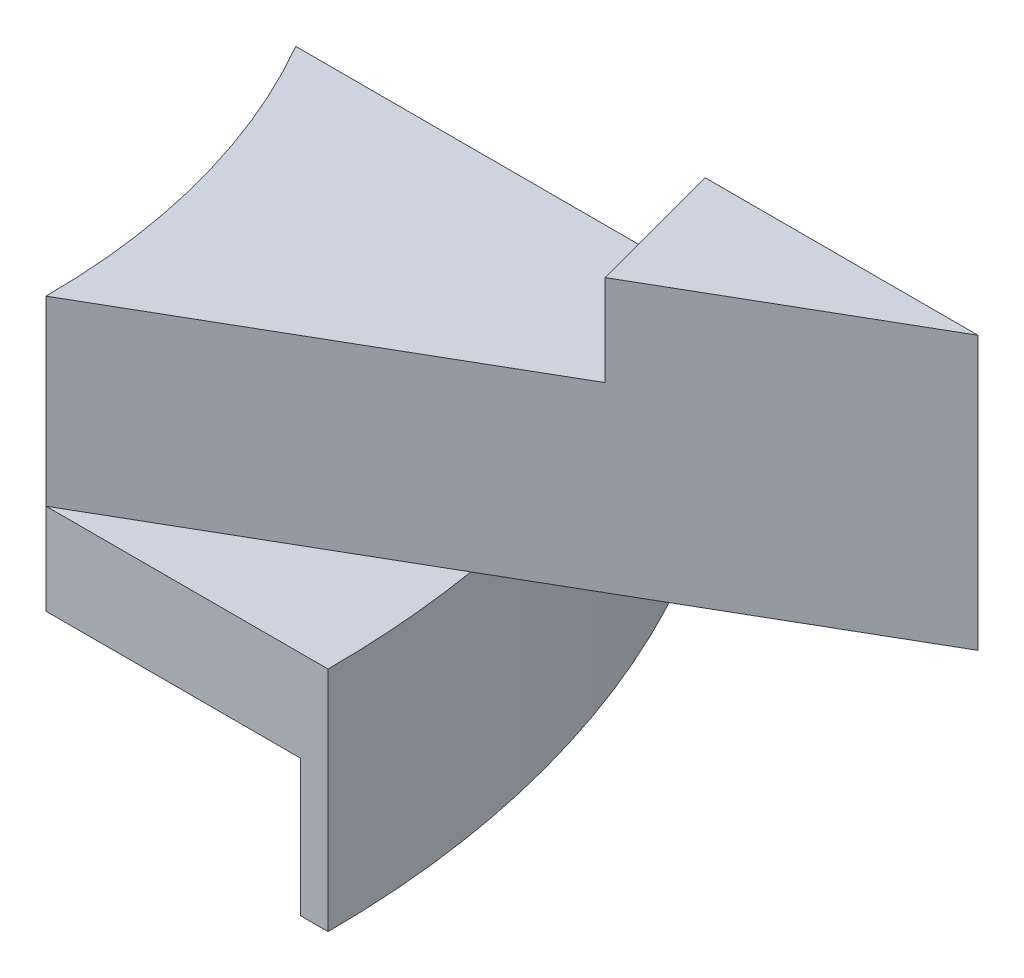
SolidWorks part; units mm, degrees
ref_plane "前视基准面" through (0, 0, 0) normal (0, 0, 1) x (1, 0, 0)
ref_plane "上视基准面" through (0, 0, 0) normal (0, 1, 0) x (1, 0, 0)
ref_plane "右视基准面" through (0, 0, 0) normal (1, 0, 0) x (0, 0, -1)
other "Configuration Table"
sketch "草图1" plane through (0, 0, 0) normal (0, 1, 0) x (1, 0, 0)
  line L1 (0, 0) -> (103, 0) construction
  line L2 (0, 0) -> (89.2006, 51.5) construction
  line L3 (64.9519, 37.5) -> (89.2006, 51.5)
  line L4 (75, 0) -> (103, 0)
  circle A0 centre (0, 0) radius 103 construction
  arc A2 (103, 0) -> (89.2006, 51.5) centre (0, 0) ccw
  arc A3 (64.9519, 37.5) -> (75, 0) centre (0, 0) cw
  dimension "D1" = 206
  dimension "D2" = 30
  dimension "D3" = 75
extrude "凸台-拉伸3" add sketch "草图1" along normal blind 10
sketch "草图5" plane through (0, 10, 0) normal (0, 1, 0) x (1, 0, 0)
  line L0 (0, 0) -> (99.4904, 26.6584) construction
  line L1 (99.4904, 26.6584) -> (204.1757, 54.7087) construction
  line L2 (64.9519, 37.5) -> (139.9519, 37.5)
  line L3 (139.9519, 37.5) -> (75, 0)
  arc A0 (103, 0) -> (89.2006, 51.5) centre (0, 0) ccw construction
  arc A1 (75, 0) -> (64.9519, 37.5) centre (0, 0) ccw
  dimension "D1" = 30
extrude "凸台-拉伸4" add sketch "草图5" along normal blind 20 contours L2 L3 A1
sketch "草图6" plane through (0, 30, 0) normal (0, 1, 0) x (1, 0, 0)
  line L0 (109.9519, 37.5) -> (139.9519, 37.5)
  line L1 (64.9519, 37.5) -> (139.9519, 37.5) construction
  line L2 (139.9519, 37.5) -> (113.9711, 22.5)
  line L3 (139.9519, 37.5) -> (75, 0) construction
  line L4 (113.9711, 22.5) -> (109.9519, 37.5)
  dimension "D1" = 30
  dimension "D2" = 30
extrude "凸台-拉伸5" add sketch "草图6" along normal blind 10
sketch "草图7" plane through (0, 10, 0) normal (0, -1, 0) x (1, 0, 0)
  line L0 (89.2006, -51.5) -> (91.7987, -53)
  line L1 (103, 0) -> (106, 0)
  arc A0 (89.2006, -51.5) -> (103, 0) centre (0, 0) ccw
  arc A1 (89.2006, -51.5) -> (103, 0) centre (0, 0) ccw construction
  arc A2 (91.7987, -53) -> (106, 0) centre (0, 0) ccw
  dimension "D1" = 3
extrude "凸台-拉伸6" add sketch "草图7" along normal blind 25
